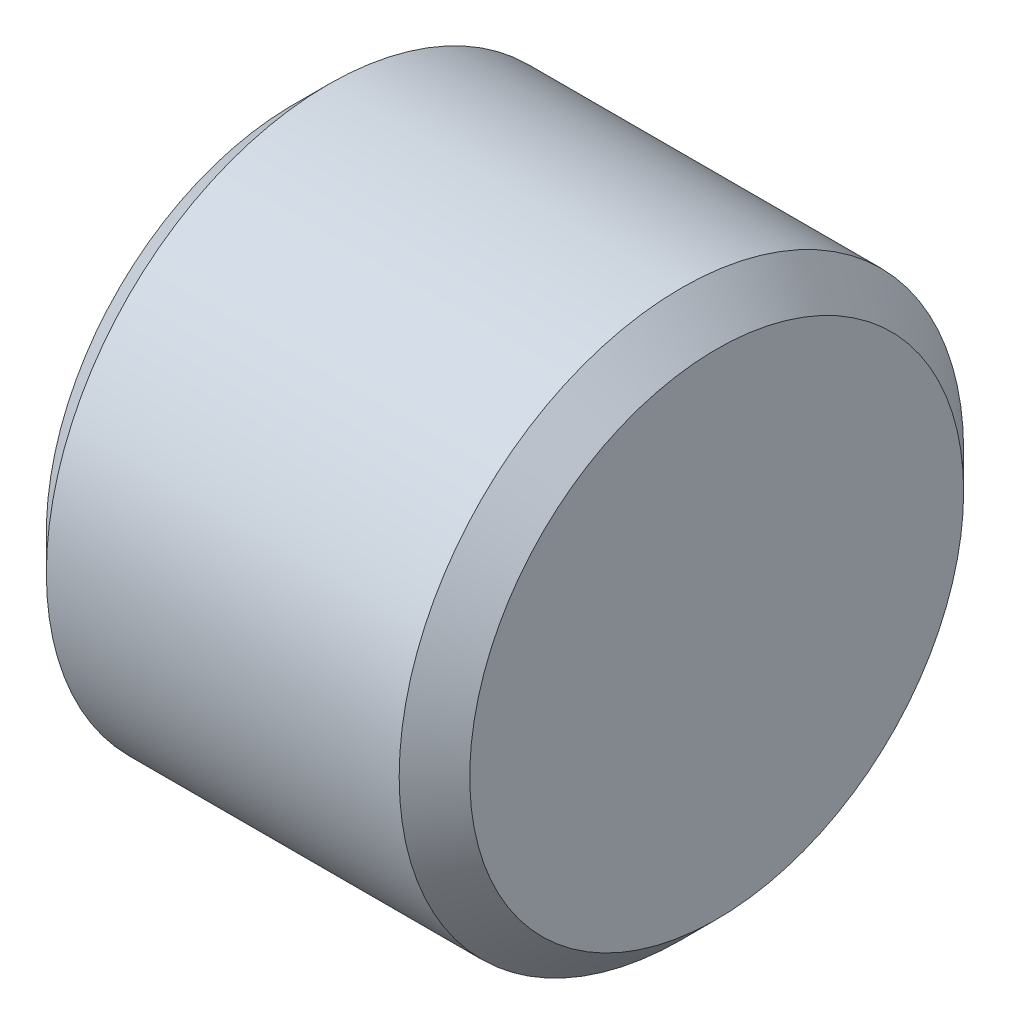
SolidWorks part; units mm, degrees
ref_plane "Front Plane" through (0, 0, 0) normal (0, 0, 1) x (1, 0, 0)
ref_plane "Top Plane" through (0, 0, 0) normal (0, 1, 0) x (1, 0, 0)
ref_plane "Right Plane" through (0, 0, 0) normal (1, 0, 0) x (0, 0, -1)
sketch "Sketch1" plane through (0, 0, 0) normal (1, 0, 0) x (0, 0, -1)
  circle A0 centre (0, 0) radius 4
  dimension "D1" = 8
extrude "Boss-Extrude1" add sketch "Sketch1" along normal blind 6
chamfer "Chamfer1" distance 0.5 angle 45 2 edges at (0, 0, -4) (6, 0, -4)
